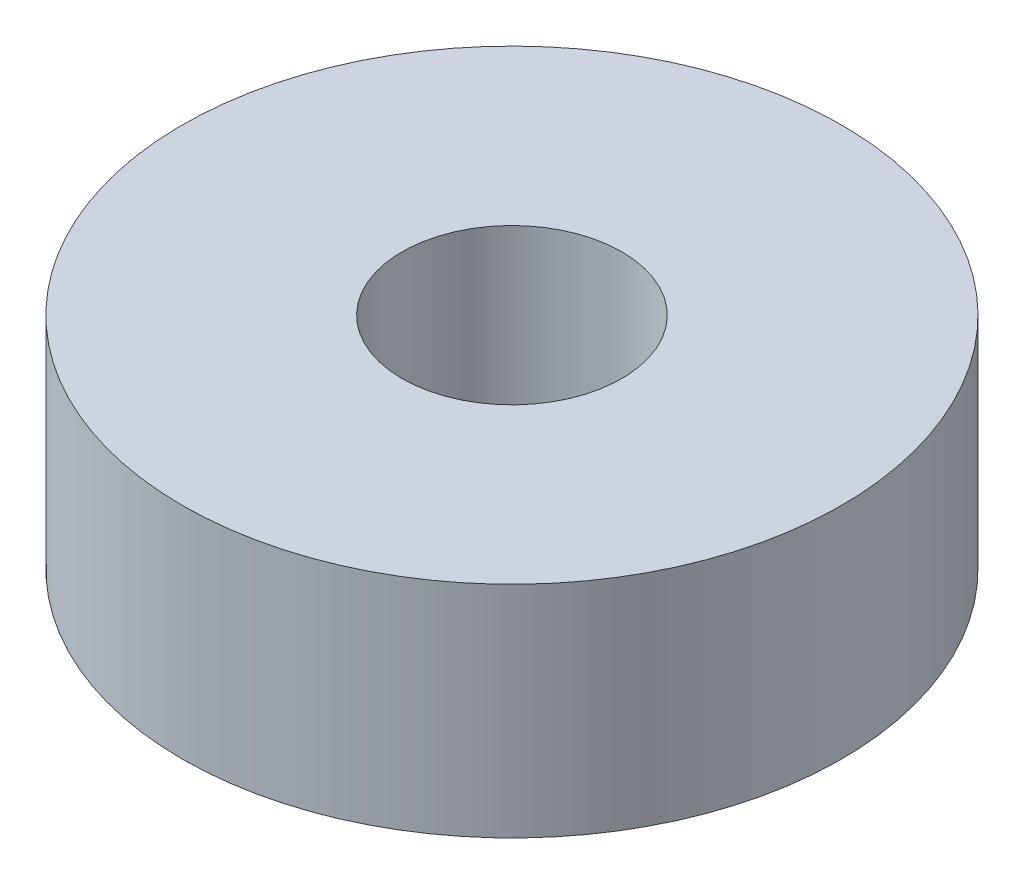
SolidWorks part; units mm, degrees
ref_plane "Front Plane" through (0, 0, 0) normal (0, 0, 1) x (1, 0, 0)
ref_plane "Top Plane" through (0, 0, 0) normal (0, 1, 0) x (1, 0, 0)
ref_plane "Right Plane" through (0, 0, 0) normal (1, 0, 0) x (0, 0, -1)
sketch "Sketch1" plane through (0, 0, 0) normal (0, 1, 0) x (1, 0, 0)
  circle A0 centre (0, 0) radius 4
  circle A1 centre (0, 0) radius 12
  dimension "D1" = 8
  dimension "D2" = 24
extrude "Boss-Extrude1" add sketch "Sketch1" along normal blind 8
